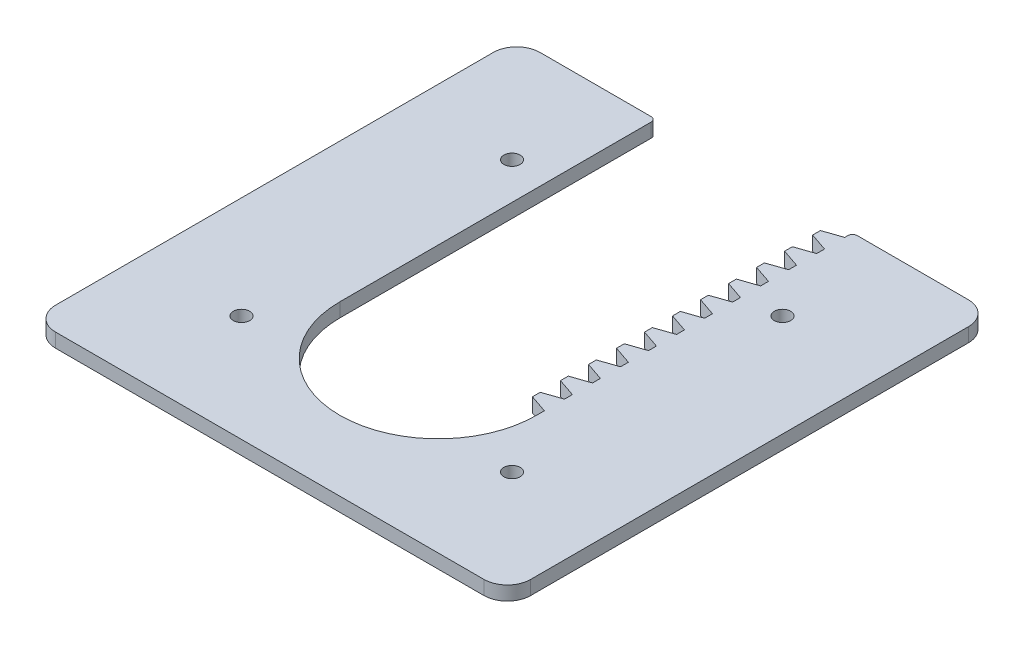
SolidWorks part; units mm, degrees
ref_plane "Front Plane" through (0, 0, 0) normal (0, 0, 1) x (1, 0, 0)
ref_plane "Top Plane" through (0, 0, 0) normal (0, 1, 0) x (1, 0, 0)
ref_plane "Right Plane" through (0, 0, 0) normal (1, 0, 0) x (0, 0, -1)
sketch "Sketch1" plane through (0, 0, 0) normal (0, 1, 0) x (1, 0, 0)
  line L0 (0, 0) -> (0, 21) construction
  line L1 (17.1887, 0) -> (0, 0) construction
  line L2 (21.0585, 3.843) -> (17.1887, 5.1665) construction
  line L3 (17.1887, 5.1665) -> (17.1887, 6.8335) construction
  line L4 (17.1887, 6.8335) -> (21.0585, 8.157) construction
  line L5 (21.0585, 9.843) -> (21.0585, 8.157) construction
  line L6 (21.0585, 9.843) -> (17.1887, 11.1665) construction
  line L7 (17.1887, 11.1665) -> (17.1887, 12.8335) construction
  line L8 (17.1887, 12.8335) -> (21.0585, 14.157) construction
  line L9 (21.0585, 15.843) -> (21.0585, 14.157) construction
  line L10 (21.0585, 15.843) -> (17.1887, 17.1665) construction
  line L11 (17.1887, 17.1665) -> (17.1887, 18.8335) construction
  line L12 (17.1887, 18.8335) -> (21.0585, 20.157) construction
  line L13 (21.0585, 21.843) -> (21.0585, 20.157) construction
  line L14 (21.0585, 21.843) -> (17.1887, 23.1665) construction
  line L15 (17.1887, 23.1665) -> (17.1887, 24.8335) construction
  line L16 (17.1887, 24.8335) -> (21.0585, 26.157) construction
  line L17 (21.0585, 27.843) -> (21.0585, 26.157) construction
  line L18 (21.0585, 27.843) -> (17.1887, 29.1665) construction
  line L19 (17.1887, 29.1665) -> (17.1887, 30.8335) construction
  line L20 (17.1887, 30.8335) -> (21.0585, 32.157) construction
  line L21 (21.0585, 33.843) -> (21.0585, 32.157) construction
  line L22 (21.0585, 33.843) -> (17.1887, 35.1665) construction
  line L23 (17.1887, 35.1665) -> (17.1887, 36.8335) construction
  line L24 (17.1887, 36.8335) -> (21.0585, 38.157) construction
  line L25 (21.0585, 39.843) -> (21.0585, 38.157) construction
  line L26 (21.0585, 39.843) -> (17.1887, 41.1665) construction
  line L27 (17.1887, 41.1665) -> (17.1887, 42.8335) construction
  line L28 (17.1887, 42.8335) -> (21.0585, 44.157) construction
  line L29 (21.0585, 45.843) -> (21.0585, 44.157) construction
  line L30 (21.0585, 45.843) -> (17.1887, 47.1665) construction
  line L31 (17.1887, 47.1665) -> (17.1887, 48.8335) construction
  line L32 (17.1887, 48.8335) -> (21.0585, 50.157) construction
  line L33 (21.0585, 51.843) -> (21.0585, 50.157) construction
  line L34 (21.0585, 51.843) -> (17.1887, 53.1665) construction
  line L35 (17.1887, 53.1665) -> (17.1887, 54.8335) construction
  line L36 (17.1887, 54.8335) -> (21.0585, 56.157) construction
  line L37 (21.0585, 57.843) -> (21.0585, 56.157) construction
  line L38 (21.0585, 57.843) -> (17.1887, 59.1665) construction
  line L39 (17.1887, 59.1665) -> (17.1887, 60.8335) construction
  line L40 (17.1887, 60.8335) -> (21.0585, 62.157) construction
  line L41 (21.0585, 62.157) -> (21.0585, 62.843) construction
  line L42 (45.8722, 63.843) -> (22.0585, 63.843) construction
  line L43 (50.8722, -34.9014) -> (50.8722, 58.843) construction
  line L44 (45.8722, -39.9014) -> (-45.8722, -39.9014) construction
  line L45 (-50.8722, 58.843) -> (-50.8722, -34.9014) construction
  line L46 (-45.8722, 63.843) -> (-22.0585, 63.843) construction
  line L47 (-21.0585, -3.843) -> (-21.0585, 62.843) construction
  line L48 (21.0585, -2.157) -> (21.0585, -3.843) construction
  line L49 (21.0585, -2.157) -> (17.1887, -0.8335) construction
  line L50 (17.1887, -0.8335) -> (17.1887, 0.8335) construction
  line L51 (17.1887, 0.8335) -> (21.0585, 2.157) construction
  line L52 (21.0585, 3.843) -> (21.0585, 2.157) construction
  line L53 (21.0585, 3.843) -> (17.1887, 5.1665)
  line L54 (17.1887, 5.1665) -> (17.1887, 6.8335)
  line L55 (17.1887, 6.8335) -> (21.0585, 8.157)
  line L56 (21.0585, 9.843) -> (21.0585, 8.157)
  line L57 (21.0585, 9.843) -> (17.1887, 11.1665)
  line L58 (17.1887, 11.1665) -> (17.1887, 12.8335)
  line L59 (17.1887, 12.8335) -> (21.0585, 14.157)
  line L60 (21.0585, 15.843) -> (21.0585, 14.157)
  line L61 (21.0585, 15.843) -> (17.1887, 17.1665)
  line L62 (17.1887, 17.1665) -> (17.1887, 18.8335)
  line L63 (17.1887, 18.8335) -> (21.0585, 20.157)
  line L64 (21.0585, 21.843) -> (21.0585, 20.157)
  line L65 (21.0585, 21.843) -> (17.1887, 23.1665)
  line L66 (17.1887, 23.1665) -> (17.1887, 24.8335)
  line L67 (17.1887, 24.8335) -> (21.0585, 26.157)
  line L68 (21.0585, 27.843) -> (21.0585, 26.157)
  line L69 (21.0585, 27.843) -> (17.1887, 29.1665)
  line L70 (17.1887, 29.1665) -> (17.1887, 30.8335)
  line L71 (17.1887, 30.8335) -> (21.0585, 32.157)
  line L72 (21.0585, 33.843) -> (21.0585, 32.157)
  line L73 (21.0585, 33.843) -> (17.1887, 35.1665)
  line L74 (17.1887, 35.1665) -> (17.1887, 36.8335)
  line L75 (17.1887, 36.8335) -> (21.0585, 38.157)
  line L76 (21.0585, 39.843) -> (21.0585, 38.157)
  line L77 (21.0585, 39.843) -> (17.1887, 41.1665)
  line L78 (17.1887, 41.1665) -> (17.1887, 42.8335)
  line L79 (17.1887, 42.8335) -> (21.0585, 44.157)
  line L80 (21.0585, 45.843) -> (21.0585, 44.157)
  line L81 (21.0585, 45.843) -> (17.1887, 47.1665)
  line L82 (17.1887, 47.1665) -> (17.1887, 48.8335)
  line L83 (17.1887, 48.8335) -> (21.0585, 50.157)
  line L84 (21.0585, 51.843) -> (21.0585, 50.157)
  line L85 (21.0585, 51.843) -> (17.1887, 53.1665)
  line L86 (17.1887, 53.1665) -> (17.1887, 54.8335)
  line L87 (17.1887, 54.8335) -> (21.0585, 56.157)
  line L88 (21.0585, 57.843) -> (21.0585, 56.157)
  line L89 (21.0585, 57.843) -> (17.1887, 59.1665)
  line L90 (17.1887, 59.1665) -> (17.1887, 60.8335)
  line L91 (17.1887, 60.8335) -> (21.0585, 62.157)
  line L92 (21.0585, 62.157) -> (21.0585, 62.843)
  line L93 (45.8722, 63.843) -> (22.0585, 63.843)
  line L94 (50.8722, -34.9014) -> (50.8722, 58.843)
  line L95 (45.8722, -39.9014) -> (-45.8722, -39.9014)
  line L96 (-50.8722, 58.843) -> (-50.8722, -34.9014)
  line L97 (-45.8722, 63.843) -> (-22.0585, 63.843)
  line L98 (-21.0585, -3.843) -> (-21.0585, 62.843)
  line L99 (21.0585, -2.157) -> (21.0585, -3.843)
  line L100 (21.0585, -2.157) -> (17.1887, -0.8335)
  line L101 (17.1887, -0.8335) -> (17.1887, 0.8335)
  line L102 (17.1887, 0.8335) -> (21.0585, 2.157)
  line L103 (21.0585, 3.843) -> (21.0585, 2.157)
  line L104 (0, 63.843) -> (0, -39.9014) construction
  line L105 (-51.8722, 11.9708) -> (51.8722, 11.9708) construction
  line L106 (0, 11.9708) -> (-51.8722, -39.9014) construction
  line L107 (51.8722, -24.9014) -> (-51.8722, -24.9014) construction
  line L108 (-36.8722, -39.9014) -> (-36.8722, 63.843) construction
  line L109 (36.8722, -39.9014) -> (36.8722, 63.843) construction
  line L110 (45.8722, -39.9014) -> (51.8722, -39.9014) construction
  line L111 (51.8722, -39.9014) -> (51.8722, 63.843) construction
  line L112 (51.8722, 63.843) -> (-51.8722, 63.843) construction
  line L113 (17.1887, 60) -> (0, 60) construction
  line L114 (-51.8722, 63.843) -> (-51.8722, -39.9014) construction
  line L115 (-51.8722, -39.9014) -> (-45.8722, -39.9014) construction
  circle A0 centre (0, 0) radius 21 construction
  circle A1 centre (0, 60) radius 21 construction
  arc A2 (22.0585, 63.843) -> (21.0585, 62.843) centre (22.0585, 62.843) ccw construction
  arc A3 (50.8722, 58.843) -> (45.8722, 63.843) centre (45.8722, 58.843) ccw construction
  arc A4 (45.8722, -39.9014) -> (50.8722, -34.9014) centre (45.8722, -34.9014) ccw construction
  arc A5 (-50.8722, -34.9014) -> (-45.8722, -39.9014) centre (-45.8722, -34.9014) ccw construction
  arc A6 (-45.8722, 63.843) -> (-50.8722, 58.843) centre (-45.8722, 58.843) ccw construction
  arc A7 (-21.0585, 62.843) -> (-22.0585, 63.843) centre (-22.0585, 62.843) ccw construction
  arc A8 (-21.0585, -3.843) -> (21.0585, -3.843) centre (0, -3.843) ccw construction
  arc A9 (22.0585, 63.843) -> (21.0585, 62.843) centre (22.0585, 62.843) ccw
  arc A10 (50.8722, 58.843) -> (45.8722, 63.843) centre (45.8722, 58.843) ccw
  arc A11 (45.8722, -39.9014) -> (50.8722, -34.9014) centre (45.8722, -34.9014) ccw
  arc A12 (-50.8722, -34.9014) -> (-45.8722, -39.9014) centre (-45.8722, -34.9014) ccw
  arc A13 (-45.8722, 63.843) -> (-50.8722, 58.843) centre (-45.8722, 58.843) ccw
  arc A14 (-21.0585, 62.843) -> (-22.0585, 63.843) centre (-22.0585, 62.843) ccw
  arc A15 (-21.0585, -3.843) -> (21.0585, -3.843) centre (0, -3.843) ccw
  circle A16 centre (28.9653, -16.9946) radius 1.75 construction
  circle A17 centre (-28.9653, -16.9946) radius 1.75 construction
  circle A18 centre (-28.9653, 40.9361) radius 1.75 construction
  circle A19 centre (28.9653, 40.9361) radius 1.75 construction
  circle A20 centre (28.9653, -16.9946) radius 1.75
  circle A21 centre (-28.9653, -16.9946) radius 1.75
  circle A22 centre (-28.9653, 40.9361) radius 1.75
  circle A23 centre (28.9653, 40.9361) radius 1.75
  circle A24 centre (0, 60) radius 21 construction
sketch "Sketch2" plane through (0, 0, 0) normal (0, 0, 1) x (1, 0, 0)
  line L0 (0, 0) -> (0, 3) construction
  line L1 (-50.8722, 0) -> (50.8722, 0)
  line L2 (-50.8722, 0) -> (-50.8722, 3)
  line L3 (-50.8722, 3) -> (50.8722, 3)
  line L4 (50.8722, 0) -> (50.8722, 3)
  line L5 (-50.8722, 3) -> (-51.8722, 3) construction
  line L6 (-51.8722, 3) -> (-51.8722, 4) construction
  line L7 (-51.8722, 4) -> (51.8722, 4) construction
  line L8 (51.8722, 4) -> (51.8722, 3) construction
  line L9 (51.8722, 3) -> (50.8722, 3) construction
  line L10 (50.8722, 0) -> (51.8722, 0) construction
  line L11 (51.8722, 0) -> (51.8722, -1) construction
  line L12 (51.8722, -1) -> (-51.8722, -1) construction
  line L13 (-51.8722, -1) -> (-51.8722, 0) construction
  line L14 (-51.8722, 0) -> (-50.8722, 0) construction
  line L15 (59.5, 48.3) -> (59.5, 45.3) construction
  dimension "D2" = 1
extrude "Boss-Extrude1" add sketch "Sketch1" along normal up to vertex (3 mm away) up to point (-50.8722, 3, 0)
ref_plane "edge" through (0, 0, -63.843) normal (0, 0, 1) x (1, 0, 0)
